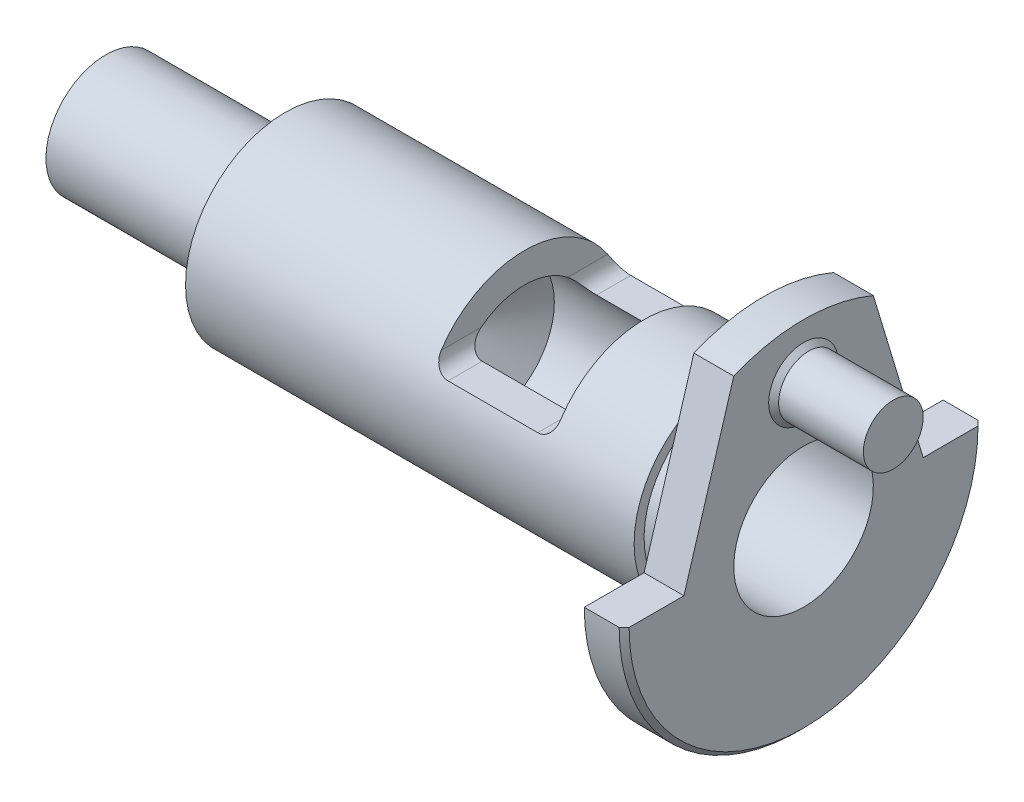
SolidWorks part; units mm, degrees
ref_plane "Plan de face" through (0, 0, 0) normal (0, 0, 1) x (1, 0, 0)
ref_plane "Plan de dessus" through (0, 0, 0) normal (0, 1, 0) x (1, 0, 0)
ref_plane "Plan de droite" through (0, 0, 0) normal (1, 0, 0) x (0, 0, -1)
sketch "Esquisse1" plane through (0, 0, 0) normal (0, 0, 1) x (1, 0, 0)
  line L0 (4.7135, 0) -> (960.77, 0) construction
  line L1 (4.7135, 0) -> (344.7135, 0)
  line L2 (344.7135, 0) -> (384.7135, 70)
  line L3 (384.7135, 70) -> (704.7135, 70)
  line L4 (704.7135, 70) -> (704.7135, 180)
  line L5 (704.7135, 180) -> (664.7135, 180)
  line L6 (664.7135, 180) -> (664.7135, 90)
  line L7 (664.7135, 90) -> (634.7135, 90)
  line L8 (634.7135, 90) -> (634.7135, 100)
  line L9 (634.7135, 100) -> (184.7135, 100)
  line L10 (184.7135, 100) -> (184.7135, 60)
  line L11 (184.7135, 60) -> (4.7135, 60)
  line L12 (4.7135, 60) -> (4.7135, 0)
  dimension "D1" = 40
  dimension "D2" = 30
  dimension "D3" = 10
  dimension "D4" = 180
  dimension "D5" = 40
  dimension "7" = 70
  dimension "D6" = 360
  dimension "D7" = 180
  dimension "D8" = 60
  dimension "D9" = 100
  dimension "D10" = 700
  dimension "D11" = 4.7135
revolve "Révolution1" add sketch "Esquisse1" angle 360 about L0
sketch "Esquisse2" plane through (0, 0, 0) normal (0, 0, 1) x (1, 0, 0)
  line L0 (634.7135, 100) -> (184.7135, 100) construction
  line L1 (424.7135, 100) -> (544.7135, 100)
  line L2 (544.7135, 100) -> (544.7135, 55)
  line L3 (529.7135, 40) -> (439.7135, 40)
  line L4 (424.7135, 55) -> (424.7135, 100)
  line L5 (634.7135, -90) -> (634.7135, 90) construction
  arc A0 (544.7135, 55) -> (529.7135, 40) centre (529.7135, 55) cw
  arc A1 (439.7135, 40) -> (424.7135, 55) centre (439.7135, 55) cw
  dimension "D1" = 15
  dimension "D2" = 120
  dimension "D3" = 90
  dimension "D4" = 60
extrude "Enlèv. mat.-Extru.1" cut sketch "Esquisse2" against normal through all both and the other way through all contours L4 L1 L2 A0 L3 A1
sketch "Esquisse4" plane through (704.7135, 0, 0) normal (1, 0, 0) x (0, 0, -1)
  line L0 (-70, 165.8312) -> (-120, 0)
  line L1 (-120, 0) -> (-180, 0)
  line L2 (0, -211.9163) -> (0, 187.8764) construction
  line L3 (120, 0) -> (180, 0)
  line L4 (70, 165.8312) -> (120, 0)
  circle A0 centre (0, 0) radius 180 construction
  circle A1 centre (0, 0) radius 180
  circle M4 centre (0, 0) radius 180
  dimension "D3" = 360
  dimension "D1" = 70
  dimension "D2" = 120
extrude "Enlèv. mat.-Extru.2" cut sketch "Esquisse4" against normal through all contours L1 L0 M4 | L4 L3 M4
sketch "Esquisse5" plane through (704.7135, 0, 0) normal (1, 0, 0) x (0, 0, -1)
  circle A0 centre (0, 125) radius 30
  arc A1 (-180, 0) -> (180, 0) centre (0, 0) ccw construction
  dimension "D1" = 60
  dimension "D3" = 55.222
  dimension "D2" = 125
extrude "Boss.-Extru.1" add sketch "Esquisse5" along normal blind 90
chamfer "Chanfrein2" distance 5 angle 45 2 edges at (704.7135, 95, 0) (704.7135, -180, 0)
